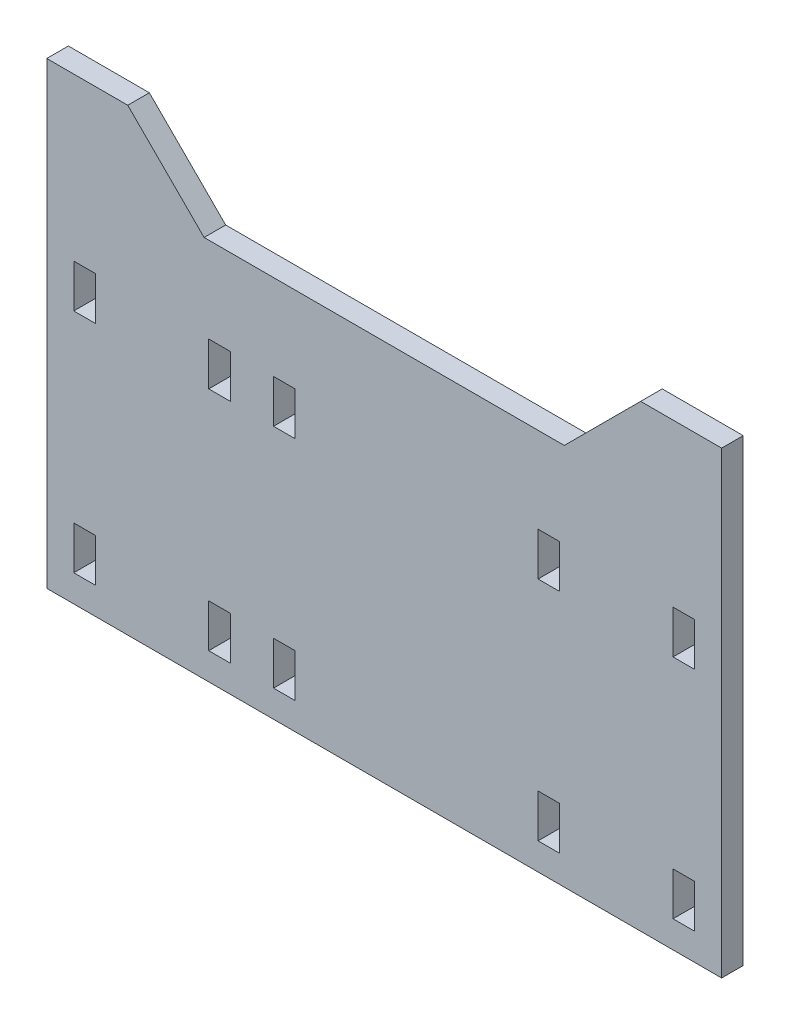
SolidWorks part; units mm, degrees
ref_plane "Front Plane" through (0, 0, 0) normal (0, 0, 1) x (1, 0, 0)
ref_plane "Top Plane" through (0, 0, 0) normal (0, 1, 0) x (1, 0, 0)
ref_plane "Right Plane" through (0, 0, 0) normal (1, 0, 0) x (0, 0, -1)
sketch "Sketch1" plane through (0, 0, 0) normal (0, 0, 1) x (1, 0, 0)
  line L0 (0, 66.0849) -> (0, -70.4198) construction
  line L6 (-38.5, 25) -> (-34.5, 25)
  line L7 (22.5, 25) -> (26.5, 25)
  line L8 (22.5, 25) -> (22.5, 17)
  line L9 (22.5, 17) -> (26.5, 17)
  line L10 (26.5, 25) -> (26.5, 17)
  line L11 (-103.5149, 0) -> (102.2922, 0) construction
  line L12 (22.5, -17) -> (26.5, -17)
  line L13 (22.5, -25) -> (22.5, -17)
  line L14 (26.5, -25) -> (26.5, -17)
  line L15 (22.5, -25) -> (26.5, -25)
  line L16 (-22.5, 25) -> (-26.5, 25)
  line L17 (-22.5, 25) -> (-22.5, 17)
  line L18 (-26.5, 25) -> (-26.5, 17)
  line L19 (-22.5, 17) -> (-26.5, 17)
  line L20 (-22.5, -17) -> (-26.5, -17)
  line L21 (-22.5, -25) -> (-22.5, -17)
  line L22 (-26.5, -25) -> (-26.5, -17)
  line L23 (-22.5, -25) -> (-26.5, -25)
  line L36 (56.5, 30) -> (56.5, -30)
  line L39 (47.5, 25) -> (51.5, 25)
  line L40 (47.5, 25) -> (47.5, 17)
  line L41 (47.5, 17) -> (51.5, 17)
  line L42 (51.5, 25) -> (51.5, 17)
  line L43 (47.5, -17) -> (51.5, -17)
  line L44 (47.5, -17) -> (47.5, -25)
  line L45 (47.5, -25) -> (51.5, -25)
  line L46 (51.5, -17) -> (51.5, -25)
  line L47 (-38.5, 25) -> (-38.5, 17)
  line L48 (-38.5, 17) -> (-34.5, 17)
  line L49 (-34.5, 25) -> (-34.5, 17)
  line L50 (-38.5, -17) -> (-34.5, -17)
  line L51 (-38.5, -17) -> (-38.5, -25)
  line L52 (-38.5, -25) -> (-34.5, -25)
  line L53 (-34.5, -17) -> (-34.5, -25)
  line L57 (-68.5, 30) -> (-68.5, -30)
  line L59 (-68.5, 30) -> (56.5, 30)
  line L60 (-63.5, 25) -> (-59.5, 25)
  line L61 (-63.5, 25) -> (-63.5, 17)
  line L62 (-63.5, 17) -> (-59.5, 17)
  line L63 (-59.5, 25) -> (-59.5, 17)
  line L64 (-63.5, -17) -> (-59.5, -17)
  line L65 (-63.5, -17) -> (-63.5, -25)
  line L66 (-63.5, -25) -> (-59.5, -25)
  line L67 (-59.5, -17) -> (-59.5, -25)
  line L68 (-68.5, -30) -> (56.5, -30)
  point P0 (0, 0)
  dimension "D2" = 60
  dimension "D3" = 8
  dimension "D5" = 4
  dimension "D6" = 8
  dimension "D7" = 45
  dimension "D8" = 21
  dimension "D9" = 21
  dimension "D10" = 5
  dimension "D12" = 5
extrude "Boss-Extrude1" add sketch "Sketch1" along normal blind 4
sketch "Sketch2" plane through (0, 0, 0) normal (0, 0, 1) x (1, 0, 0)
  line L0 (-68.5, 30) -> (-68.5, 55)
  line L1 (-68.5, 55) -> (-53.5, 55)
  line L2 (-53.5, 55) -> (-39.3579, 40.8579)
  line L7 (56.5, 30) -> (-68.5, 30)
  line L8 (41.5, 55) -> (56.5, 55)
  line L9 (56.5, 55) -> (56.5, 30)
  line L10 (41.5, 55) -> (27.3579, 40.8579)
  line L11 (27.3579, 40.8579) -> (-39.3579, 40.8579)
  dimension "D1" = 25
  dimension "D2" = 15
  dimension "D3" = 135
  dimension "D4" = 20
extrude "Boss-Extrude2" add sketch "Sketch2" along normal blind 4
